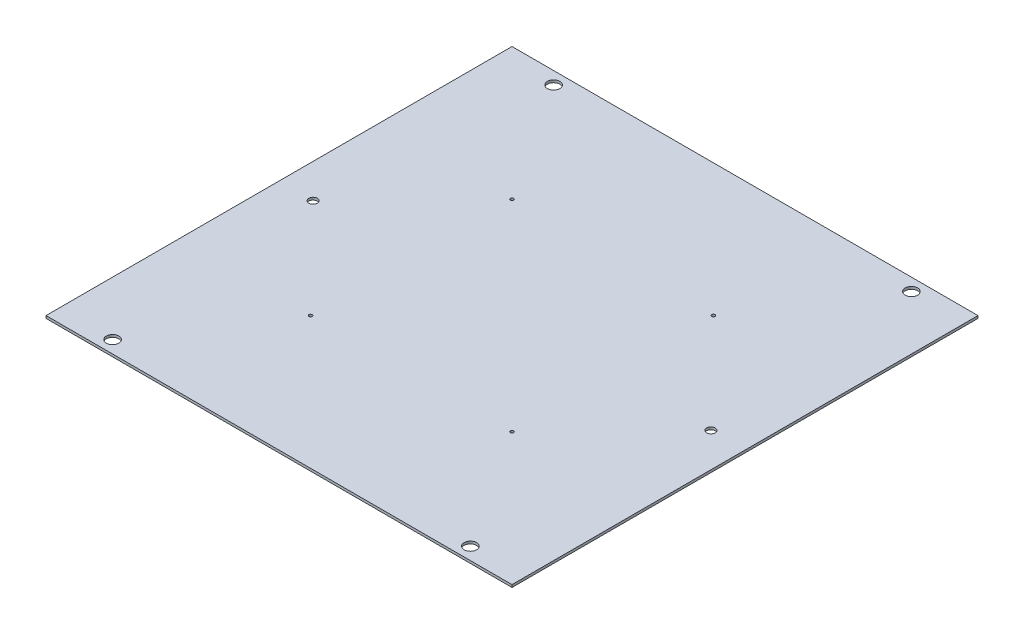
SolidWorks part; units mm, degrees
ref_plane "Front Plane" through (0, 0, 0) normal (0, 0, 1) x (1, 0, 0)
ref_plane "Top Plane" through (0, 0, 0) normal (0, 1, 0) x (1, 0, 0)
ref_plane "Right Plane" through (0, 0, 0) normal (1, 0, 0) x (0, 0, -1)
sketch "Sketch1" plane through (0, 0, 0) normal (0, 1, 0) x (1, 0, 0)
  line L1 (0, 0) -> (560, 0)
  line L2 (0, 0) -> (0, 560)
  line L3 (0, 560) -> (560, 560)
  line L4 (560, 0) -> (560, 560)
  dimension "D1" = 560
  dimension "D2" = 560
extrude "Boss-Extrude1" add sketch "Sketch1" along normal blind 3
hole_wizard "Ø4.0mm Dowel Hole1" positions "Sketch2" profile "Sketch3" hole size "Ø4.0" standard "ANSI Metric" end condition through all
sketch "Sketch2" plane through (0, 3, 0) normal (0, 1, 0) x (1, 0, 0)
  point P0 (159, 159)
  point P3 (401, 159)
  point P6 (401, 401)
  point P9 (159, 401)
sketch "Sketch3" plane through (159, 3, -159) normal (1, 0, 0) x (0, 0, 1)
  line L0 (0, 0) -> (0, 3)
  line L1 (0, 3) -> (2, 3)
  line L2 (2, 3) -> (2, 0)
  line L5 (2, 0) -> (0, 0)
  line L11 (0, -6.35) -> (0, 107.95) construction
  dimension "Thru Hole Dia." = 4
  dimension "Thru Hole Depth" = 3
sketch "Sketch5" plane through (0, 3, 0) normal (0, 1, 0) x (1, 0, 0)
  line L0 (0, 560) -> (0, 0) construction
  line L1 (0, 0) -> (560, 0) construction
  line L2 (560, 0) -> (560, 560) construction
  circle A0 centre (41, 280) radius 5.15
  circle A1 centre (519, 280) radius 5.15
  dimension "D1" = 41
  dimension "D2" = 10.3
  dimension "D3" = 280
  dimension "D4" = 10.3
  dimension "D5" = 41
  dimension "D6" = 280
extrude "Cut-Extrude1" cut sketch "Sketch5" against normal blind 10
sketch "Sketch6" plane through (0, 3, 0) normal (0, 1, 0) x (1, 0, 0)
  line L0 (0, 0) -> (560, 0) construction
  line L1 (560, 0) -> (560, 560) construction
  line L2 (0, 280) -> (560, 280) construction
  line L3 (0, 560) -> (0, 0) construction
  circle A0 centre (495, 15) radius 7.5
  circle A1 centre (65, 15) radius 7.5
  circle A2 centre (495, 545) radius 7.5
  circle A3 centre (65, 545) radius 7.5
  dimension "D1" = 15
  dimension "D2" = 15
  dimension "D3" = 15
  dimension "D4" = 15
  dimension "D5" = 430
  dimension "D6" = 65
extrude "Cut-Extrude2" cut sketch "Sketch6" against normal blind 10
